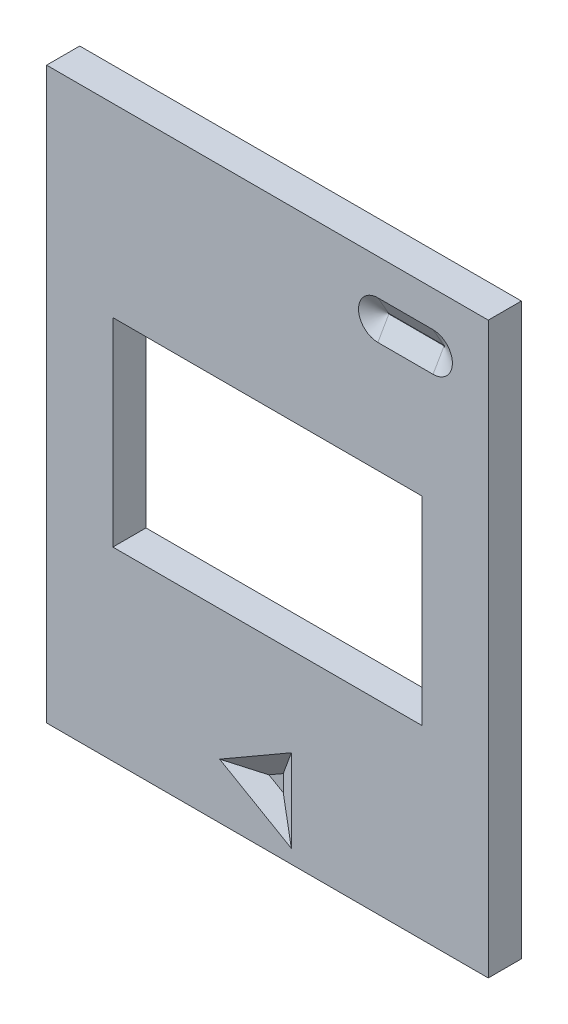
SolidWorks part; units mm, degrees
material "ABS"
ref_plane "Front Plane" through (0, 0, 0) normal (0, 0, 1) x (1, 0, 0)
ref_plane "Top Plane" through (0, 0, 0) normal (0, 1, 0) x (1, 0, 0)
ref_plane "Right Plane" through (0, 0, 0) normal (1, 0, 0) x (0, 0, -1)
sketch "Sketch1" plane through (0, 0, 0) normal (0, 0, 1) x (1, 0, 0)
  line L0 (40, 51.6) -> (0, 51.6)
  line L1 (0, 51.6) -> (0, 0)
  line L2 (0, 0) -> (40, 0)
  line L3 (40, 0) -> (40, 51.6)
extrude "Boss-Extrude1" add sketch "Sketch1" against normal blind 3
sketch "Sketch2" plane through (0, 0, -3) normal (0, 0, -1) x (-1, 0, 0)
  line L0 (-6, 16.8) -> (-6, 34.8)
  line L1 (-6, 34.8) -> (-34, 34.8)
  line L2 (-34, 34.8) -> (-34, 16.8)
  line L3 (-34, 16.8) -> (-6, 16.8)
extrude "Cut-Extrude1" cut sketch "Sketch2" against normal through all
sketch "Sketch3" plane through (0, 0, 0) normal (0, 0, 1) x (1, 0, 0)
  line L0 (35, 48.35) -> (30, 48.35)
  line L1 (30, 44.85) -> (35, 44.85)
  arc A0 (30, 48.35) -> (30, 44.85) centre (30, 46.6) ccw
  arc A1 (35, 44.85) -> (35, 48.35) centre (35, 46.6) ccw
extrude "Cut-Extrude2" cut sketch "Sketch3" against normal blind 1 draft 60
sketch "Sketch4" plane through (0, 0, 0) normal (0, 0, 1) x (1, 0, 0)
  line L0 (15.6699, 5) -> (22.1651, 1.25)
  line L1 (22.1651, 1.25) -> (22.1651, 8.75)
  line L2 (22.1651, 8.75) -> (15.6699, 5)
extrude "Cut-Extrude3" cut sketch "Sketch4" against normal blind 1 draft 60
